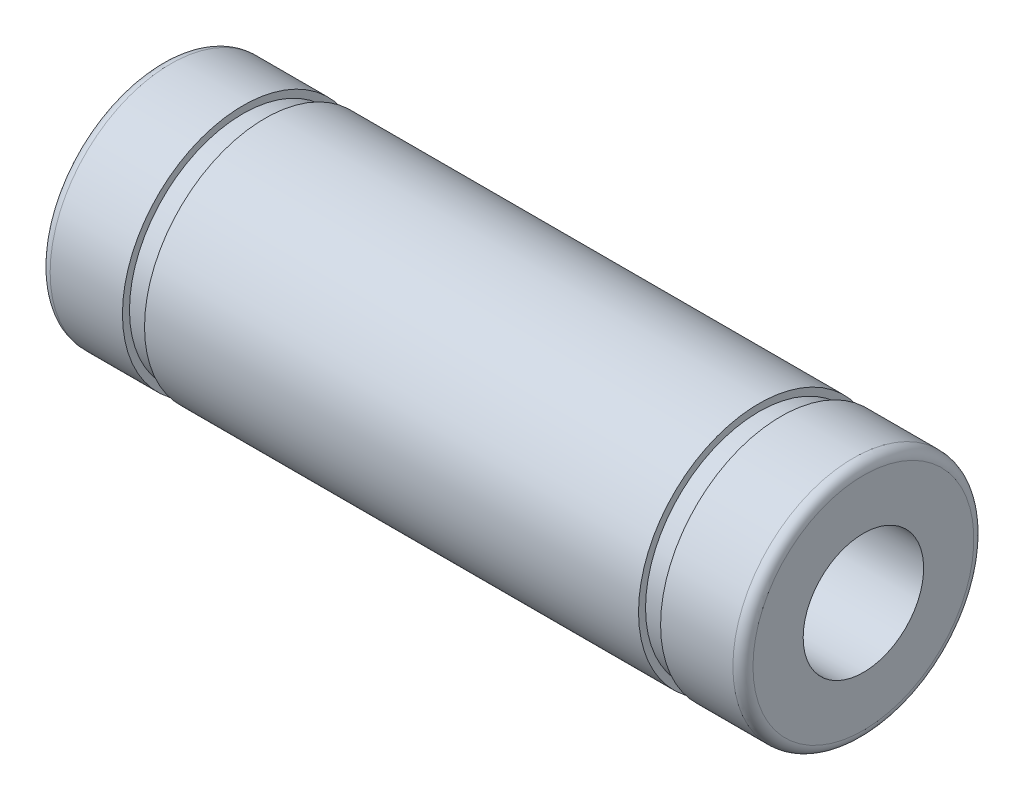
SolidWorks part; units mm, degrees
ref_plane "Front Plane" through (0, 0, 0) normal (0, 0, 1) x (1, 0, 0)
ref_plane "Top Plane" through (0, 0, 0) normal (0, 1, 0) x (1, 0, 0)
ref_plane "Right Plane" through (0, 0, 0) normal (1, 0, 0) x (0, 0, -1)
sketch "Sketch2" plane through (0, 0, 0) normal (0, 1, 0) x (1, 0, 0)
  line L0 (0, 0) -> (11.4368, 0) construction
  line L1 (0, 0) -> (0, 6) construction
  line L2 (-12.3, 6) -> (12.3, 6)
  line L3 (12.3, 6) -> (12.3, 5.65)
  line L4 (12.3, 5.65) -> (13.4, 5.65)
  line L5 (13.4, 5.65) -> (13.4, 6)
  line L6 (13.4, 6) -> (17.5, 6)
  line L7 (17.5, 6) -> (17.5, 3)
  line L8 (17.5, 3) -> (-17.5, 3)
  line L9 (-17.5, 6) -> (-17.5, 3)
  line L10 (-13.4, 6) -> (-17.5, 6)
  line L11 (-13.4, 5.65) -> (-13.4, 6)
  line L12 (-12.3, 5.65) -> (-13.4, 5.65)
  line L13 (-12.3, 6) -> (-12.3, 5.65)
  point P12 (0, 3)
  dimension "D1" = 6
  dimension "D2" = 5.65
  dimension "D3" = 1.1
  dimension "D4" = 13.4
  dimension "D5" = 17.5
  dimension "D6" = 3
revolve "Revolve1" add sketch "Sketch2" angle 360 about L0
fillet "Fillet1" radius 0.5 2 edges at (-17.5, 0, 6) (17.5, 0, 6)
